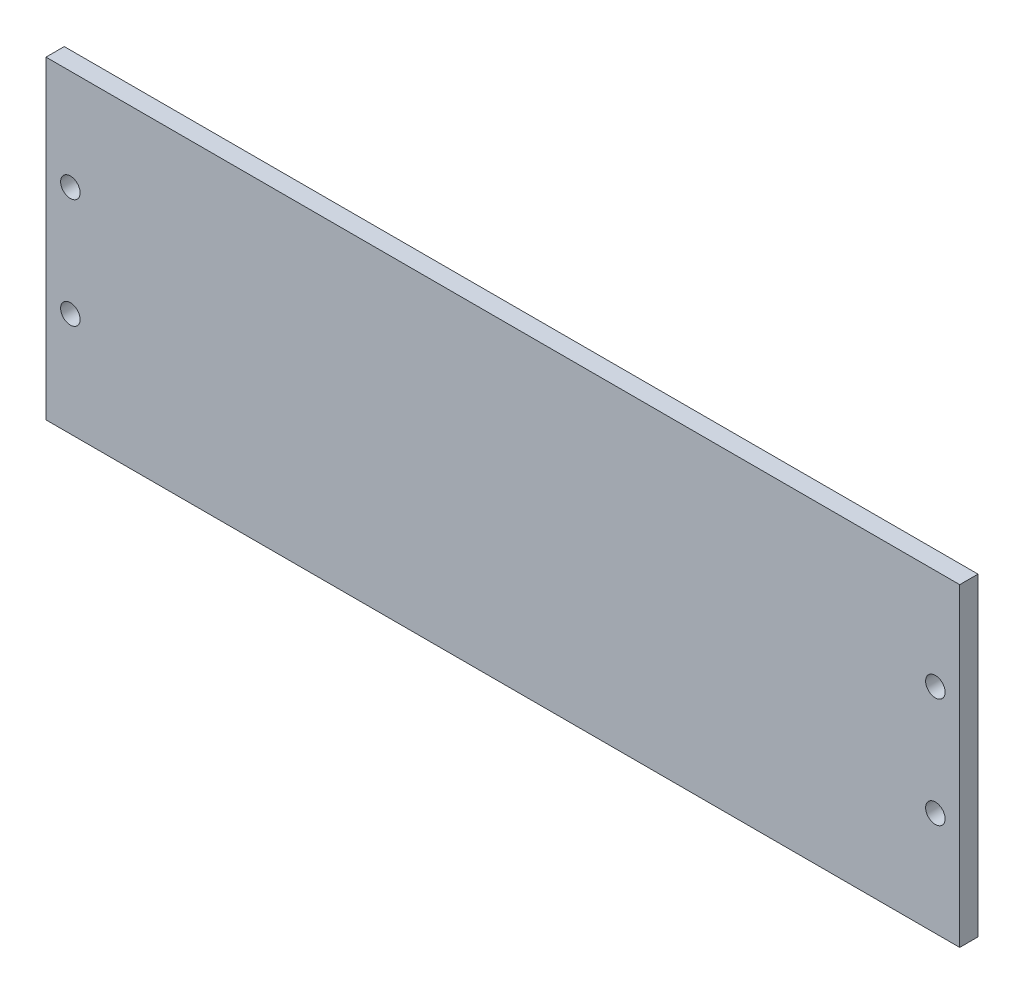
SolidWorks part; units mm, degrees
ref_plane "前视基准面" through (0, 0, 0) normal (0, 0, 1) x (1, 0, 0)
ref_plane "上视基准面" through (0, 0, 0) normal (0, 1, 0) x (1, 0, 0)
ref_plane "右视基准面" through (0, 0, 0) normal (1, 0, 0) x (0, 0, -1)
other "Configuration Table"
sketch "草图1" plane through (0, 0, 0) normal (0, 0, 1) x (1, 0, 0)
  line L4 (-47.1117, 42.1397) -> (-47.1117, 93.7183)
  line L5 (-47.1117, 42.1397) -> (102.8883, 42.1397)
  line L6 (-47.1117, 93.7183) -> (102.8883, 93.7183)
  line L7 (102.8883, 42.1397) -> (102.8883, 93.7183)
  line L8 (27.8883, 34.5904) -> (27.8883, 103.3137) construction
  circle A0 centre (-43.1117, 77.2183) radius 1.6
  circle A1 centre (-43.1117, 59.2183) radius 1.6
  circle A2 centre (98.8883, 59.2183) radius 1.6
  circle A3 centre (98.8883, 77.2183) radius 1.6
  dimension "D3" = 3.2
  dimension "D4" = 3.2
  dimension "D1" = 150
  dimension "D2" = 75
extrude "凸台-拉伸1" add sketch "草图1" against normal blind 3
